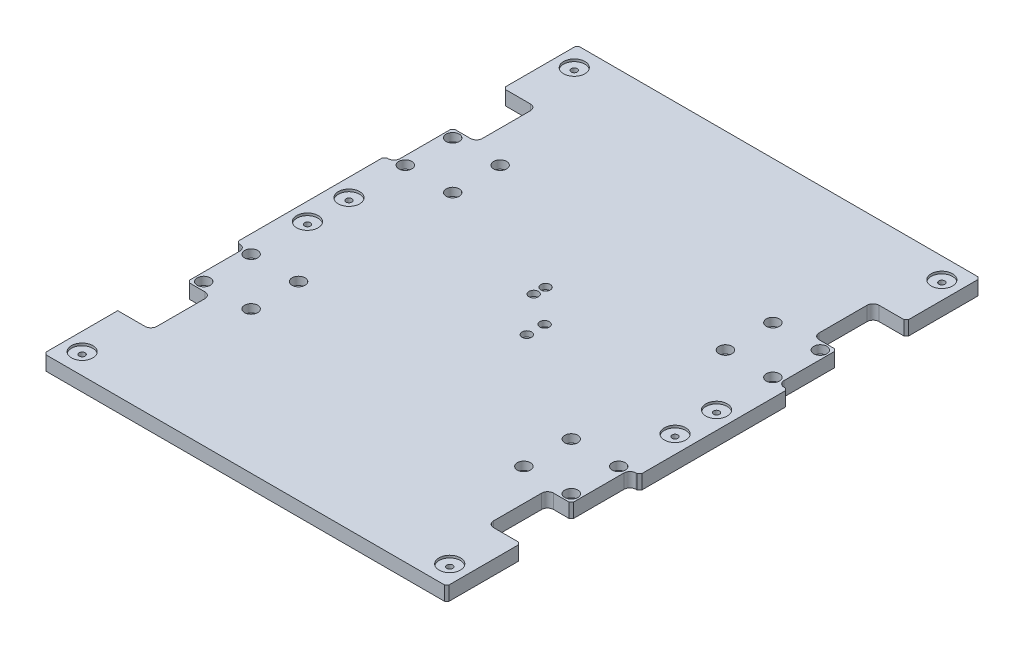
SolidWorks part; units mm, degrees
material "电木板A级"
ref_plane "前视" through (0, 0, 0) normal (0, 0, 1) x (1, 0, 0)
ref_plane "上视" through (0, 0, 0) normal (0, 1, 0) x (1, 0, 0)
ref_plane "右视" through (0, 0, 0) normal (1, 0, 0) x (0, 0, -1)
sketch "草图1" plane through (0, 0, 0) normal (0, 1, 0) x (1, 0, 0)
  line L1 (-170, -225) -> (170, -225)
  line L2 (-170, -225) -> (-170, 225)
  line L3 (-170, 225) -> (170, 225)
  line L4 (170, -225) -> (170, 225)
  line L5 (-170, -225) -> (170, 225) construction
  line L6 (-170, 225) -> (170, -225) construction
  point P0 (0, 0)
  dimension "D1" = 340
  dimension "D2" = 450
extrude "凸台-拉伸1" add sketch "草图1" along normal blind 12
hole_wizard "打孔尺寸根据内六角圆柱头螺钉的类型3" positions "草图3" profile "草图2" counterbore size "M6" standard "Gb" end condition through all
sketch "草图3" plane through (0, 12, 0) normal (0, 1, 0) x (1, 0, 0)
  line L0 (0, -225) -> (0, 0) construction
  line L1 (-170, -225) -> (170, -225) construction
  line L2 (0, 0) -> (170, 0) construction
  line L3 (170, -225) -> (170, 225) construction
  point P20 (-115, 65)
  point P21 (-115, 105)
  point P22 (-155, 105)
  point P23 (-155, 65)
  point P35 (155, 65)
  point P36 (155, 105)
  point P37 (115, 105)
  point P38 (115, 65)
  point P39 (115, -65)
  point P40 (115, -105)
  point P41 (155, -105)
  point P42 (155, -65)
  point P43 (-155, -65)
  point P44 (-155, -105)
  point P45 (-115, -105)
  point P46 (-115, -65)
  dimension "D1" = 40
  dimension "D2" = 40
  dimension "D3" = 270
  dimension "D4" = 130
sketch "草图2" plane through (-115, 12, -65) normal (1, 0, 0) x (0, 0, 1)
  line L0 (0, 0) -> (0, 12)
  line L1 (0, 12) -> (3.3, 12)
  line L3 (3.3, 12) -> (3.3, 6.8)
  line L4 (3.3, 6.8) -> (5.5, 6.8)
  line L5 (5.5, 6.8) -> (5.5, 0)
  line L7 (5.5, 0) -> (0, 0)
  line L11 (0, -6.35) -> (0, 107.95) construction
  dimension "通孔孔直径" = 6.6
  dimension "通孔孔深度" = 12
  dimension "柱形沉头孔直径" = 11
  dimension "柱形沉头孔深度" = 6.8
hole_wizard "打孔尺寸根据内六角圆柱头螺钉的类型3" positions "草图5" profile "草图4" counterbore size "M4" standard "Gb" end condition through all
sketch "草图5" plane through (0, 12, 0) normal (0, 1, 0) x (1, 0, 0)
  line L0 (38.9, 0) -> (170, 0) construction
  line L2 (-170, -225) -> (170, -225) construction
  line L3 (170, -225) -> (170, 225) construction
  line L4 (-170, -225) -> (170, -225) construction
  line L5 (170, -225) -> (170, 225) construction
  point P0 (20, 7.5)
  point P8 (20, -7.5)
  point P9 (0, -225)
  point P14 (170, 0)
  point P17 (-6.7, 25)
  point P21 (-6.7, 35)
  point P24 (0, -225)
  dimension "D1" = 15
  dimension "D2" = 20
  dimension "D3" = 25
  dimension "D4" = 6.7
  dimension "D5" = 10
sketch "草图4" plane through (20, 12, -7.5) normal (1, 0, 0) x (0, 0, 1)
  line L0 (0, 0) -> (0, 12)
  line L1 (0, 12) -> (2.25, 12)
  line L3 (2.25, 12) -> (2.25, 4.6)
  line L4 (2.25, 4.6) -> (4, 4.6)
  line L5 (4, 4.6) -> (4, 0)
  line L7 (4, 0) -> (0, 0)
  line L11 (0, -6.35) -> (0, 107.95) construction
  dimension "通孔孔直径" = 4.5
  dimension "通孔孔深度" = 12
  dimension "柱形沉头孔直径" = 8
  dimension "柱形沉头孔深度" = 4.6
hole_wizard "M6 螺纹孔1" positions "草图9" profile "草图8" tap size "M6" standard "Gb" end condition through all
sketch "草图9" plane through (-174.7145, 0, 28.6293) normal (0, 1, 0) x (1, 0, 0)
  line L0 (174.7145, -196.3707) -> (174.7145, 28.6293) construction
  line L1 (4.7145, -196.3707) -> (344.7145, -196.3707) construction
  line L2 (174.7145, 28.6293) -> (4.7145, 28.6293) construction
  line L3 (4.7145, 253.6293) -> (4.7145, -196.3707) construction
  point P0 (19.7145, 236.1293)
  point P2 (19.7145, 46.1293)
  point P17 (329.7145, 46.1293)
  point P18 (329.7145, 236.1293)
  point P21 (329.7145, -178.8707)
  point P22 (329.7145, 11.1293)
  point P23 (19.7145, 11.1293)
  point P24 (19.7145, -178.8707)
  dimension "D1" = 310
  dimension "D2" = 190
  dimension "D3" = 35
sketch "草图8" plane through (-155, 0, -207.5) normal (1, 0, 0) x (0, 0, -1)
  line L0 (0, 0) -> (0, 12)
  line L1 (0, 12) -> (2.5, 12)
  line L2 (2.5, 12) -> (2.5, 0)
  line L5 (2.5, 0) -> (0, 0)
  line L11 (0, -6.35) -> (0, 107.95) construction
  dimension "通孔螺纹孔钻头直径" = 5
  dimension "通孔螺纹孔钻头深度" = 12
cosmetic thread "孔螺蚊线1" parameters "D2"=6
cosmetic thread "孔螺蚊线2" parameters "D2"=6
cosmetic thread "孔螺蚊线3" parameters "D2"=6
cosmetic thread "孔螺蚊线4" parameters "D2"=6
cosmetic thread "孔螺蚊线5" parameters "D2"=6
cosmetic thread "孔螺蚊线6" parameters "D2"=6
cosmetic thread "孔螺蚊线7" parameters "D2"=6
cosmetic thread "孔螺蚊线8" parameters "D2"=6
hole_wizard "孔1" positions "草图12" profile "草图11" legacy
sketch "草图12" plane through (0, 12, 0) normal (0, 1, 0) x (1, 0, 0)
  line L0 (0, 225) -> (0, -77.6062) construction
  line L1 (170, 225) -> (-170, 225) construction
  line L2 (-170, 0) -> (-50.1476, 0) construction
  line L3 (-170, 225) -> (-170, -225) construction
  point P0 (-155, 17.5)
  point P3 (-155, 207.5)
  point P22 (155, 207.5)
  point P23 (155, 17.5)
  point P30 (155, -17.5)
  point P31 (155, -207.5)
  point P32 (-155, -207.5)
  point P33 (-155, -17.5)
sketch "草图11" plane through (-155, 12, -17.5) normal (1, 0, 0) x (0, 0, 1)
  line L0 (0, 0) -> (0, 2)
  line L1 (0, 2) -> (9, 2)
  line L2 (9, 2) -> (9, 0)
  line L3 (9, 0) -> (0, 0)
  line L4 (0, 110) -> (0, -10) construction
  dimension "直径" = 18
  dimension "深度" = 2
sketch "草图13" plane through (0, 12, 0) normal (0, 1, 0) x (1, 0, 0)
  line L0 (0, 225) -> (0, 0) construction
  line L1 (170, 225) -> (-170, 225) construction
  line L2 (0, 0) -> (170, 0) construction
  line L3 (170, -225) -> (170, 225) construction
  line L4 (-155, 207.5) -> (-155, 17.5) construction
  line L5 (-155, 112.5) -> (-40.5767, 112.5) construction
  line L6 (-170, 225) -> (-170, -225) construction
  line L7 (-167, 62.5) -> (-170, 62.5)
  line L8 (-162, 67.5) -> (-162, 112)
  line L9 (-147, 162.5) -> (-170, 162.5)
  line L10 (-170, 62.5) -> (-170, 162.5)
  line L11 (-162, 62.5) -> (-170, 162.5) construction
  line L12 (-162, 162.5) -> (-170, 62.5) construction
  line L13 (162, 162.5) -> (170, 62.5) construction
  line L14 (162, 62.5) -> (170, 162.5) construction
  line L15 (142, 117) -> (142, 157.5)
  line L16 (162, 112) -> (147, 112)
  line L17 (170, 62.5) -> (170, 162.5)
  line L18 (147, 162.5) -> (170, 162.5)
  line L19 (162, 67.5) -> (162, 112)
  line L20 (167, 62.5) -> (170, 62.5)
  line L21 (162, -62.5) -> (170, -162.5) construction
  line L22 (162, -162.5) -> (170, -62.5) construction
  line L23 (-162, -162.5) -> (-170, -62.5) construction
  line L24 (-162, -62.5) -> (-170, -162.5) construction
  line L25 (-155, -112.5) -> (-40.5767, -112.5) construction
  line L26 (-142, -117) -> (-142, -157.5)
  line L27 (-162, -112) -> (-147, -112)
  line L28 (167, -62.5) -> (170, -62.5)
  line L29 (162, -67.5) -> (162, -112)
  line L30 (147, -162.5) -> (170, -162.5)
  line L31 (170, -62.5) -> (170, -162.5)
  line L32 (-162, 112) -> (-147, 112)
  line L33 (-142, 117) -> (-142, 157.5)
  line L34 (162, -112) -> (147, -112)
  line L35 (142, -117) -> (142, -157.5)
  line L36 (-170, -62.5) -> (-170, -162.5)
  line L37 (-147, -162.5) -> (-170, -162.5)
  line L38 (-162, -67.5) -> (-162, -112)
  line L39 (-167, -62.5) -> (-170, -62.5)
  circle A0 centre (-155, 105) radius 5.5 construction
  arc A1 (-167, 62.5) -> (-162, 67.5) centre (-167, 67.5) ccw
  circle A3 centre (-155, 105) radius 5.5 construction
  arc A4 (142, 157.5) -> (147, 162.5) centre (147, 157.5) cw
  arc A5 (147, 112) -> (142, 117) centre (147, 117) cw
  arc A6 (167, 62.5) -> (162, 67.5) centre (167, 67.5) cw
  arc A7 (-142, -157.5) -> (-147, -162.5) centre (-147, -157.5) cw
  arc A8 (-147, -112) -> (-142, -117) centre (-147, -117) cw
  arc A9 (167, -62.5) -> (162, -67.5) centre (167, -67.5) ccw
  arc A10 (-147, 112) -> (-142, 117) centre (-147, 117) ccw
  arc A11 (-142, 157.5) -> (-147, 162.5) centre (-147, 157.5) ccw
  arc A12 (147, -112) -> (142, -117) centre (147, -117) ccw
  arc A13 (142, -157.5) -> (147, -162.5) centre (147, -157.5) ccw
  arc A14 (-167, -62.5) -> (-162, -67.5) centre (-167, -67.5) cw
  point P14 (-166, 112.5)
  point P43 (142, 162.5)
  point P44 (166, 112.5)
  point P70 (-142, 162.5)
  point P82 (-142, -162.5)
  point P83 (166, -112.5)
  point P84 (142, -162.5)
  point P85 (-166, -112.5)
  dimension "D3" = 5
  dimension "D5" = 5
  dimension "D6" = 20
  dimension "D1" = 7
  dimension "D2" = 100
  dimension "D4" = 7
extrude "切除-拉伸1" cut sketch "草图13" against normal through all
chamfer "倒角1" distance 2 angle 45 15 edges at (-170, 6, -225) (170, 6, -225) (170, 6, 225) (-170, 6, 225) (-170, 6, -62.5) (-170, 6, -162.5) (170, 6, -162.5) (162, 6, -112) (170, 6, -62.5) (170, 6, 62.5) (170, 6, 162.5) (162, 6, 112) (-162, 6, 112) (-170, 6, 62.5) (-162, 6, -112)
